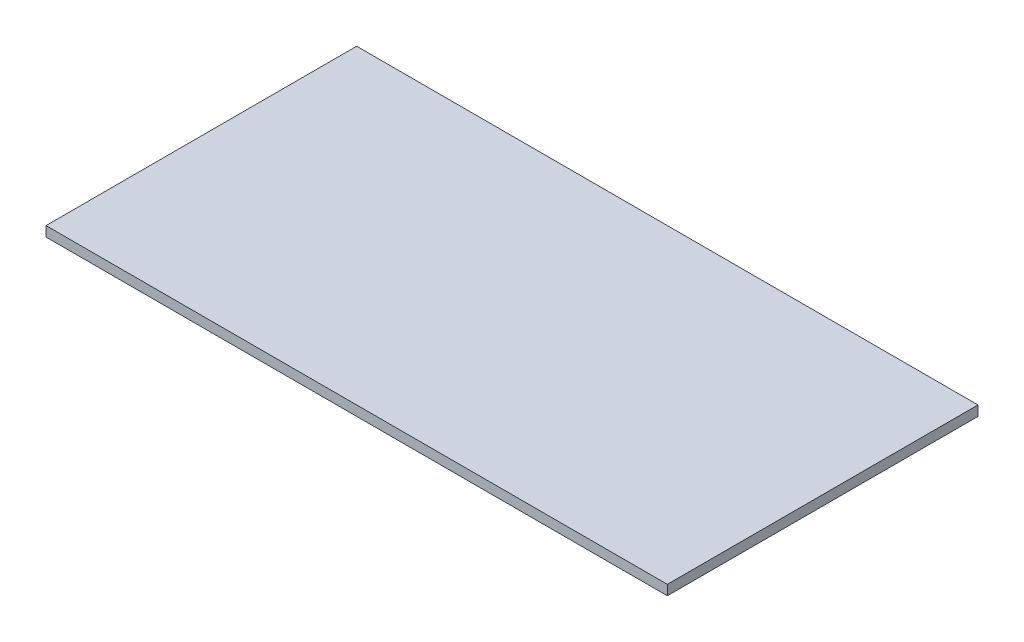
SolidWorks part; units mm, degrees
ref_plane "Front Plane" through (0, 0, 0) normal (0, 0, 1) x (1, 0, 0)
ref_plane "Top Plane" through (0, 0, 0) normal (0, 1, 0) x (1, 0, 0)
ref_plane "Right Plane" through (0, 0, 0) normal (1, 0, 0) x (0, 0, -1)
sketch "Sketch1" plane through (0, 0, 0) normal (0, 1, 0) x (1, 0, 0)
  line L1 (0, 0) -> (100, 0)
  line L2 (0, 0) -> (0, 50)
  line L3 (0, 50) -> (100, 50)
  line L4 (100, 0) -> (100, 50)
  dimension "D1" = 50
  dimension "D2" = 100
extrude "Boss-Extrude1" add sketch "Sketch1" along normal blind 1.6
